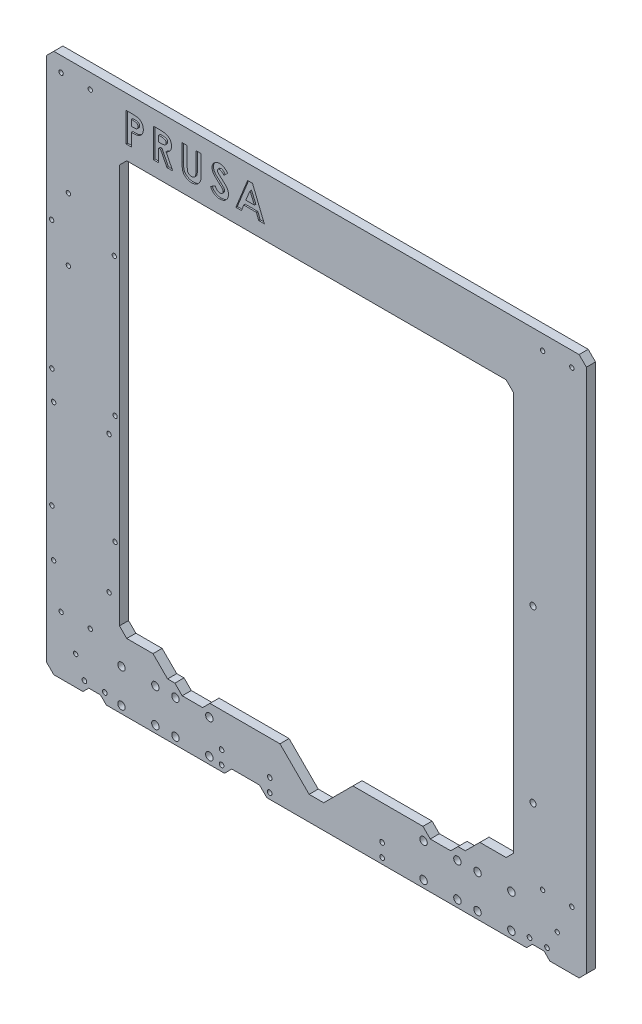
SolidWorks part; units mm, degrees
material "6063-O, Extruded Rod (SS)"
ref_plane "Front Plane" through (0, 0, 0) normal (0, 0, 1) x (1, 0, 0)
ref_plane "Top Plane" through (0, 0, 0) normal (0, 1, 0) x (1, 0, 0)
ref_plane "Right Plane" through (0, 0, 0) normal (1, 0, 0) x (0, 0, -1)
sketch "Sketch1" plane through (0, 0, 0) normal (0, 0, 1) x (1, 0, 0)
  line L0 (162, 177.023) -> (141.977, 157)
  line L1 (141.977, 157) -> (125, 157)
  line L2 (125, 157) -> (101.5, 180.5)
  line L3 (101.5, 189.5) -> (125, 213)
  line L4 (125, 213) -> (141.977, 213)
  line L5 (141.977, 213) -> (162, 192.977)
  line L6 (251.5, 210.0147) -> (240.9853, 220.5294)
  line L7 (240.9853, 220.5294) -> (224.0147, 220.5294)
  line L8 (224.0147, 220.5294) -> (197, 193.5147)
  line L9 (197, 176.4853) -> (224.0147, 149.4706)
  line L10 (224.0147, 149.4706) -> (240.9853, 149.4706)
  line L11 (240.9853, 149.4706) -> (251.5, 159.9853)
  line L12 (184.4001, 296) -> (225.4001, 255)
  line L13 (225.4001, 255) -> (241.5147, 255)
  line L14 (241.5147, 255) -> (282.5147, 296)
  line L15 (282.5147, 296) -> (287.4852, 296)
  line L16 (287.4852, 296) -> (291, 292.4852)
  line L17 (291, 292.4852) -> (291, 287.5147)
  line L18 (291, 287.5147) -> (253, 249.5147)
  line L19 (253, 249.5147) -> (253, 226.667)
  line L20 (253, 226.667) -> (291, 188.667)
  line L21 (291, 188.667) -> (291, 181.333)
  line L22 (291, 181.333) -> (253, 143.333)
  line L23 (253, 143.333) -> (253, 120.4853)
  line L24 (253, 120.4853) -> (291, 82.4853)
  line L25 (291, 82.4853) -> (291, 77.5148)
  line L26 (291, 77.5148) -> (287.4852, 74)
  line L27 (287.4852, 74) -> (282.5147, 74)
  line L28 (282.5147, 74) -> (241.5147, 115)
  line L29 (241.5147, 115) -> (225.4001, 115)
  line L30 (225.4001, 115) -> (184.4001, 74)
  line L31 (184.4001, 74) -> (175.5999, 74)
  line L32 (175.5999, 74) -> (134.5999, 115)
  line L33 (134.5999, 115) -> (113.4853, 115)
  line L34 (113.4853, 115) -> (72.4853, 74)
  line L35 (72.4853, 74) -> (67.5148, 74)
  line L36 (67.5148, 74) -> (64, 77.5148)
  line L37 (64, 77.5148) -> (64, 82.4853)
  line L38 (64, 82.4853) -> (91, 109.4853)
  line L39 (91, 109.4853) -> (91, 123)
  line L40 (91, 123) -> (81.5, 132.5)
  line L41 (81.5, 132.5) -> (81.5, 163.7609)
  line L42 (81.5, 163.7609) -> (64, 181.2609)
  line L43 (64, 188.7391) -> (81.5, 206.2391)
  line L44 (81.5, 206.2391) -> (81.5, 237.5)
  line L45 (81.5, 237.5) -> (91, 247)
  line L46 (91, 247) -> (91, 260.5147)
  line L47 (91, 260.5147) -> (64, 287.5147)
  line L48 (64, 287.5147) -> (64, 292.4852)
  line L49 (64, 292.4852) -> (67.5148, 296)
  line L50 (67.5148, 296) -> (72.4853, 296)
  line L51 (72.4853, 296) -> (113.4853, 255)
  line L52 (113.4853, 255) -> (134.5999, 255)
  line L53 (134.5999, 255) -> (175.5999, 296)
  line L54 (175.5999, 296) -> (184.4001, 296)
  line L55 (143, 246.4158) -> (143, 229.5663)
  line L56 (143, 229.5663) -> (159.5663, 213)
  line L57 (159.5663, 213) -> (199.5147, 213)
  line L58 (199.5147, 213) -> (216, 229.4853)
  line L59 (216, 229.4853) -> (216, 247.4296)
  line L60 (216, 247.4296) -> (183.6826, 279.747)
  line L61 (183.6826, 279.747) -> (176.3174, 279.7332)
  line L62 (176.3174, 279.7332) -> (143, 246.4158)
  line L63 (143, 123.5842) -> (143, 140.4337)
  line L64 (143, 140.4337) -> (159.5663, 157)
  line L65 (159.5663, 157) -> (199.5147, 157)
  line L66 (199.5147, 157) -> (216, 140.5147)
  line L67 (216, 140.5147) -> (216, 122.5704)
  line L68 (216, 122.5704) -> (183.6826, 90.253)
  line L69 (183.6826, 90.253) -> (176.3174, 90.2668)
  line L70 (176.3174, 90.2668) -> (143, 123.5842)
  line L71 (101.5, 226.75) -> (101.5, 213.25)
  line L72 (271.5, 191.75) -> (271.5, 178.25)
  line L73 (101.5, 156.75) -> (101.5, 143.25)
  line L74 (91.5, 226.75) -> (91.5, 213.25)
  line L75 (261.5, 191.75) -> (261.5, 178.25)
  line L76 (91.5, 156.75) -> (91.5, 143.25)
  line L77 (93.6792, 358.4107) -> (93.6792, 347.8262)
  line L78 (93.6792, 347.8262) -> (93.9406, 345.7354)
  line L79 (93.9406, 345.7354) -> (94.4633, 344.2327)
  line L80 (94.4633, 344.2327) -> (95.182, 343.1873)
  line L81 (95.182, 343.1873) -> (96.1846, 341.9648)
  line L82 (96.1846, 341.9648) -> (97.8105, 341.4329)
  line L83 (97.8105, 341.4329) -> (99.6248, 341.0966)
  line L84 (99.6248, 341.0966) -> (101.977, 341.3579)
  line L85 (101.977, 341.3579) -> (104.0024, 342.4033)
  line L86 (104.0024, 342.4033) -> (105.1131, 344.2327)
  line L87 (105.1131, 344.2327) -> (105.5705, 346.7155)
  line L88 (105.5705, 346.7155) -> (105.5705, 349.1983)
  line L89 (105.5705, 349.1983) -> (105.5705, 358.4107)
  line L90 (79.8932, 349.3289) -> (80.0892, 349.3289)
  line L91 (80.0892, 349.3289) -> (81.0039, 348.8063)
  line L92 (81.0039, 348.8063) -> (82.0493, 347.4342)
  line L93 (82.0493, 347.4342) -> (86.4922, 341.0966)
  line L94 (73.5556, 341.1619) -> (73.5556, 358.4107)
  line L95 (73.5556, 358.4107) -> (80.6119, 358.4107)
  line L96 (80.6119, 358.4107) -> (82.768, 357.7574)
  line L97 (82.768, 357.7574) -> (83.8134, 356.7773)
  line L98 (83.8134, 356.7773) -> (84.5321, 355.4706)
  line L99 (84.5321, 355.4706) -> (84.8588, 353.7065)
  line L100 (84.8588, 353.7065) -> (84.5321, 352.0078)
  line L101 (84.5321, 352.0078) -> (83.6827, 350.5703)
  line L102 (83.6827, 350.5703) -> (82.5067, 349.8517)
  line L103 (82.5067, 349.8517) -> (81.3306, 349.525)
  line L104 (81.3306, 349.525) -> (79.8932, 349.3289)
  line L105 (79.8932, 349.3289) -> (78.1291, 349.3289)
  line L106 (78.1291, 349.3289) -> (73.5556, 349.3289)
  line L107 (113.0897, 345.4442) -> (114.2004, 343.4842)
  line L108 (114.2004, 343.4842) -> (116.6178, 341.8507)
  line L109 (116.6178, 341.8507) -> (118.9699, 341.1974)
  line L110 (118.9699, 341.1974) -> (122.4328, 341.7201)
  line L111 (122.4328, 341.7201) -> (124.0662, 343.0268)
  line L112 (124.0662, 343.0268) -> (125.2422, 345.1176)
  line L113 (125.2422, 345.1176) -> (125.2422, 346.359)
  line L114 (125.2422, 346.359) -> (124.9156, 347.4697)
  line L115 (124.9156, 347.4697) -> (123.7395, 348.7764)
  line L116 (123.7395, 348.7764) -> (122.5635, 349.2991)
  line L117 (122.5635, 349.2991) -> (116.7485, 351.0632)
  line L118 (116.7485, 351.0632) -> (115.0497, 352.1739)
  line L119 (115.0497, 352.1739) -> (114.0044, 353.4153)
  line L120 (114.0044, 353.4153) -> (113.8737, 354.5914)
  line L121 (113.8737, 354.5914) -> (114.135, 356.3554)
  line L122 (114.135, 356.3554) -> (115.3764, 357.6622)
  line L123 (115.3764, 357.6622) -> (117.4672, 358.4462)
  line L124 (117.4672, 358.4462) -> (120.0807, 358.5769)
  line L125 (120.0807, 358.5769) -> (122.8248, 357.8582)
  line L126 (122.8248, 357.8582) -> (123.9355, 356.8128)
  line L127 (123.9355, 356.8128) -> (124.3929, 355.5714)
  line L128 (130.9954, 341.0312) -> (137.9864, 358.5414)
  line L129 (137.9864, 358.5414) -> (139.0972, 358.5414)
  line L130 (139.0972, 358.5414) -> (145.9575, 341.0312)
  line L131 (143.9343, 346.1951) -> (133.0803, 346.1927)
  line L132 (55, 341.1619) -> (55, 358.4107)
  line L133 (55, 358.4107) -> (62.0563, 358.4107)
  line L134 (62.0563, 358.4107) -> (64.2125, 357.7574)
  line L135 (64.2125, 357.7574) -> (65.2578, 356.7773)
  line L136 (65.2578, 356.7773) -> (65.9765, 355.4706)
  line L137 (65.9765, 355.4706) -> (66.3032, 353.7065)
  line L138 (66.3032, 353.7065) -> (65.9765, 352.0078)
  line L139 (65.9765, 352.0078) -> (65.1272, 350.5703)
  line L140 (65.1272, 350.5703) -> (63.9511, 349.8517)
  line L141 (63.9511, 349.8517) -> (62.7751, 349.525)
  line L142 (62.7751, 349.525) -> (61.3376, 349.3289)
  line L143 (61.3376, 349.3289) -> (59.5735, 349.3289)
  line L144 (59.5735, 349.3289) -> (55, 349.3289)
  line L145 (251.5, 210.0147) -> (251.5, 159.9853)
  line L146 (197, 193.5147) -> (197, 176.4853)
  line L147 (64, 188.7391) -> (64, 181.2609)
  line L148 (101.5, 189.5) -> (101.5, 180.5)
  line L149 (162, 192.977) -> (162, 177.023)
  line L150 (102.1, 142.75) -> (102, 142.75)
  line L151 (272.1, 177.75) -> (272, 177.75)
  line L152 (102.1, 212.75) -> (102, 212.75)
  line L153 (90.9, 142.75) -> (91, 142.75)
  line L154 (260.9, 177.75) -> (261, 177.75)
  line L155 (90.9, 212.75) -> (91, 212.75)
  line L156 (102, 142.75) -> (101.5, 143.25)
  line L157 (272, 177.75) -> (271.5, 178.25)
  line L158 (102, 212.75) -> (101.5, 213.25)
  line L159 (91, 142.75) -> (91.5, 143.25)
  line L160 (261, 177.75) -> (261.5, 178.25)
  line L161 (91, 212.75) -> (91.5, 213.25)
  line L162 (102.1, 157.25) -> (102, 157.25)
  line L163 (272.1, 192.25) -> (272, 192.25)
  line L164 (102.1, 227.25) -> (102, 227.25)
  line L165 (90.9, 157.25) -> (91, 157.25)
  line L166 (260.9, 192.25) -> (261, 192.25)
  line L167 (90.9, 227.25) -> (91, 227.25)
  line L168 (101.5, 156.75) -> (102, 157.25)
  line L169 (271.5, 191.75) -> (272, 192.25)
  line L170 (101.5, 226.75) -> (102, 227.25)
  line L171 (91.5, 156.75) -> (91, 157.25)
  line L172 (261.5, 191.75) -> (261, 192.25)
  line L173 (91.5, 226.75) -> (91, 227.25)
  line L174 (90.9, 163.25) -> (102.1, 163.25)
  line L175 (260.9, 198.25) -> (272.1, 198.25)
  line L176 (90.9, 233.25) -> (102.1, 233.25)
  line L177 (90.9, 136.75) -> (102.1, 136.75)
  line L178 (260.9, 171.75) -> (272.1, 171.75)
  line L179 (90.9, 206.75) -> (102.1, 206.75)
  arc A0 (102.1, 206.75) -> (102.1, 212.75) centre (102.1, 209.75) ccw
  arc A1 (272.1, 171.75) -> (272.1, 177.75) centre (272.1, 174.75) ccw
  arc A2 (102.1, 136.75) -> (102.1, 142.75) centre (102.1, 139.75) ccw
  arc A3 (90.9, 142.75) -> (90.9, 136.75) centre (90.9, 139.75) ccw
  arc A4 (90.9, 212.75) -> (90.9, 206.75) centre (90.9, 209.75) ccw
  arc A5 (260.9, 177.75) -> (260.9, 171.75) centre (260.9, 174.75) ccw
  arc A6 (102.1, 157.25) -> (102.1, 163.25) centre (102.1, 160.25) ccw
  arc A7 (102.1, 227.25) -> (102.1, 233.25) centre (102.1, 230.25) ccw
  arc A8 (272.1, 192.25) -> (272.1, 198.25) centre (272.1, 195.25) ccw
  arc A9 (90.9, 163.25) -> (90.9, 157.25) centre (90.9, 160.25) ccw
  arc A10 (260.9, 198.25) -> (260.9, 192.25) centre (260.9, 195.25) ccw
  arc A11 (90.9, 233.25) -> (90.9, 227.25) centre (90.9, 230.25) ccw
  circle A12 centre (318.6, 4.9) radius 2.55
  circle A13 centre (318.6, 28.1) radius 2.55
  circle A14 centre (295.4, 28.1) radius 2.55
  circle A15 centre (295.4, 4.9) radius 2.55
  circle A16 centre (281.6, 4.9) radius 2.55
  circle A17 centre (258.4, 4.9) radius 2.55
  circle A18 centre (258.4, 28.1) radius 2.55
  circle A19 centre (281.6, 28.1) radius 2.55
  circle A20 centre (111.6, 4.9) radius 2.55
  circle A21 centre (111.6, 28.1) radius 2.55
  circle A22 centre (88.4, 28.1) radius 2.55
  circle A23 centre (88.4, 4.9) radius 2.55
  circle A24 centre (74.6, 4.9) radius 2.55
  circle A25 centre (74.6, 28.1) radius 2.55
  circle A26 centre (51.4, 28.1) radius 2.55
  circle A27 centre (51.4, 4.9) radius 2.55
  circle A28 centre (360, 39.8) radius 1.5
  circle A29 centre (10, 39.8) radius 1.5
  circle A30 centre (340, 359.8) radius 1.5
  circle A31 centre (30, 39.8) radius 1.5
  circle A32 centre (42.9, 67.8) radius 1.5
  circle A33 centre (340, 39.8) radius 1.5
  circle A34 centre (10, 359.8) radius 1.5
  circle A35 centre (350, 19.8) radius 1.5
  circle A36 centre (47, 99.8) radius 1.5
  circle A37 centre (3.7, 181.1) radius 1.5
  circle A38 centre (20, 19.8) radius 1.5
  circle A39 centre (4.9, 67.8) radius 1.5
  circle A40 centre (360, 359.8) radius 1.5
  circle A41 centre (42.9, 161.8) radius 1.5
  circle A42 centre (3.7, 99.8) radius 1.5
  circle A43 centre (30, 359.8) radius 1.5
  circle A44 centre (47, 174.7) radius 1.5
  circle A45 centre (4.9, 161.8) radius 1.5
  circle A46 centre (46.5, 269.3) radius 1.5
  circle A47 centre (15, 247.8) radius 1.5
  circle A48 centre (3.5, 269.3) radius 1.5
  circle A49 centre (15, 290.8) radius 1.5
  circle A50 centre (180, 80) radius 1.5
  circle A51 centre (180, 290) radius 1.5
  circle A52 centre (285, 80) radius 1.5
  circle A53 centre (70, 290) radius 1.5
  circle A54 centre (285, 290) radius 1.5
  circle A55 centre (70, 185) radius 1.5
  circle A56 centre (180, 185) radius 1.5
  circle A57 centre (285, 185) radius 1.5
  circle A58 centre (256.5, 185) radius 1.6
  circle A59 centre (276.5, 185) radius 1.6
  circle A60 centre (106.5, 220) radius 1.6
  circle A61 centre (106.5, 150) radius 1.6
  circle A62 centre (86.5, 220) radius 1.6
  circle A63 centre (86.5, 150) radius 1.6
  circle A64 centre (70, 80) radius 1.5
  circle A65 centre (181.5, 165.5) radius 1.5
  circle A66 centre (181.5, 204.5) radius 1.5
  circle A67 centre (40, 7) radius 1.6
  circle A68 centre (331, 7) radius 1.6
  circle A69 centre (343, 7) radius 1.6
  circle A70 centre (120, 13) radius 1.6
  circle A71 centre (120, 4) radius 1.6
  circle A72 centre (230, 13) radius 1.6
  circle A73 centre (230, 4) radius 1.6
  circle A74 centre (333.4, 205) radius 2.1
  circle A75 centre (333.4, 88) radius 2.1
  circle A76 centre (26, 7) radius 1.6
  circle A77 centre (153, 13) radius 1.6
  circle A78 centre (153, 4) radius 1.6
  spline S0 degree 2 poles (5, 370) (2.5, 367.5) (0, 365) knots 1472.868668 1472.868668 1472.868668 1479.939736 1479.939736 1479.939736
  spline S1 degree 2 poles (365, 370) (185, 370) (5, 370) knots 1112.868668 1112.868668 1112.868668 1472.868668 1472.868668 1472.868668
  spline S2 degree 2 poles (370, 365) (367.5, 367.5) (365, 370) knots 1105.7976 1105.7976 1105.7976 1112.868668 1112.868668 1112.868668
  spline S3 degree 2 poles (370, 5) (370, 185) (370, 365) knots 745.7976 745.7976 745.7976 1105.7976 1105.7976 1105.7976
  spline S4 degree 2 poles (365, 0) (367.5, 2.5) (370, 5) knots 738.726533 738.726533 738.726533 745.7976 745.7976 745.7976
  spline S5 degree 2 poles (345, 0) (355, 0) (365, 0) knots 718.726533 718.726533 718.726533 738.726533 738.726533 738.726533
  spline S6 degree 2 poles (341, 4) (343, 2) (345, 0) knots 710.241251 710.241251 710.241251 718.726533 718.726533 718.726533
  spline S7 degree 2 poles (333, 4) (337, 4) (341, 4) knots 704.241251 704.241251 704.241251 710.241251 710.241251 710.241251
  spline S8 degree 2 poles (329, 0) (331, 2) (333, 4) knots 698.584397 698.584397 698.584397 704.241251 704.241251 704.241251
  spline S9 degree 2 poles (151, 0) (240, 0) (329, 0) knots 507.584397 507.584397 507.584397 698.584397 698.584397 698.584397
  spline S10 degree 2 poles (146, 5) (148.5, 2.5) (151, 0) knots 501.927543 501.927543 501.927543 507.584397 507.584397 507.584397
  spline S11 degree 2 poles (127, 5) (136.5, 5) (146, 5) knots 487.927543 487.927543 487.927543 501.927543 501.927543 501.927543
  spline S12 degree 2 poles (122, 0) (124.5, 2.5) (127, 5) knots 482.270688 482.270688 482.270688 487.927543 487.927543 487.927543
  spline S13 degree 2 poles (41, 0) (81.5, 0) (122, 0) knots 407.270688 407.270688 407.270688 482.270688 482.270688 482.270688
  spline S14 degree 2 poles (37, 4) (39, 2) (41, 0) knots 401.613834 401.613834 401.613834 407.270688 407.270688 407.270688
  spline S15 degree 2 poles (29, 4) (33, 4) (37, 4) knots 395.613834 395.613834 395.613834 401.613834 401.613834 401.613834
  spline S16 degree 2 poles (25, 0) (27, 2) (29, 4) knots 387.128553 387.128553 387.128553 395.613834 395.613834 395.613834
  spline S17 degree 2 poles (5, 0) (15, 0) (25, 0) knots 367.128553 367.128553 367.128553 387.128553 387.128553 387.128553
  spline S18 degree 2 poles (0, 5) (2.5, 2.5) (5, 0) knots 360.191742 360.191742 360.191742 367.128553 367.128553 367.128553
  spline S19 degree 2 poles (0, 365) (0, 185) (0, 5) knots 0 0 0 360.191742 360.191742 360.191742
  spline S20 degree 2 poles (93, 31.5) (100, 31.5) (107, 31.5) knots 1110.421356 1110.421356 1110.421356 1117.046356 1117.046356 1117.046356
  spline S21 degree 2 poles (88, 36.5) (90.5, 34) (93, 31.5) knots 1103.350288 1103.350288 1103.350288 1110.421356 1110.421356 1110.421356
  spline S22 degree 2 poles (83, 36.5) (85.5, 36.5) (88, 36.5) knots 1098.350288 1098.350288 1098.350288 1103.350288 1103.350288 1103.350288
  spline S23 degree 2 poles (73, 46.5) (78, 41.5) (83, 36.5) knots 1084.208153 1084.208153 1084.208153 1098.350288 1098.350288 1098.350288
  spline S24 degree 2 poles (55, 46.5) (64, 46.5) (73, 46.5) knots 1066.208153 1066.208153 1066.208153 1084.208153 1084.208153 1084.208153
  spline S25 degree 2 poles (50, 51.5) (52.5, 49) (55, 46.5) knots 1059.137085 1059.137085 1059.137085 1066.208153 1066.208153 1066.208153
  spline S26 degree 2 poles (50, 325) (50, 188.25) (50, 51.5) knots 787.637085 787.637085 787.637085 1059.137085 1059.137085 1059.137085
  spline S27 degree 2 poles (55, 330) (52.5, 327.5) (50, 325) knots 780.566017 780.566017 780.566017 787.637085 787.637085 787.637085
  spline S28 degree 2 poles (315, 330) (185, 330) (55, 330) knots 520.566017 520.566017 520.566017 780.566017 780.566017 780.566017
  spline S29 degree 2 poles (320, 325) (317.5, 327.5) (315, 330) knots 513.494949 513.494949 513.494949 520.566017 520.566017 520.566017
  spline S30 degree 2 poles (320, 51.5) (320, 188.25) (320, 325) knots 241.994949 241.994949 241.994949 513.494949 513.494949 513.494949
  spline S31 degree 2 poles (315, 46.5) (317.5, 49) (320, 51.5) knots 234.923882 234.923882 234.923882 241.994949 241.994949 241.994949
  spline S32 degree 2 poles (297, 46.5) (306, 46.5) (315, 46.5) knots 216.923882 216.923882 216.923882 234.923882 234.923882 234.923882
  spline S33 degree 2 poles (287, 36.5) (292, 41.5) (297, 46.5) knots 202.781746 202.781746 202.781746 216.923882 216.923882 216.923882
  spline S34 degree 2 poles (282, 36.5) (284.5, 36.5) (287, 36.5) knots 197.781746 197.781746 197.781746 202.781746 202.781746 202.781746
  spline S35 degree 2 poles (277, 31.5) (279.5, 34) (282, 36.5) knots 190.710678 190.710678 190.710678 197.781746 197.781746 197.781746
  spline S36 degree 2 poles (263, 31.5) (264, 31.5) (265, 31.5) (270, 31.5) (275, 31.5) (276, 31.5) (277, 31.5) knots 176.710678 176.710678 176.710678 178.710678 178.710678 188.710678 188.710678 190.710678 190.710678 190.710678
  spline S37 degree 2 poles (258, 36.5) (260.5, 34) (263, 31.5) knots 169.63961 169.63961 169.63961 176.710678 176.710678 176.710678
  spline S38 degree 2 poles (210, 36.5) (211.75, 36.5) (213.5, 36.5) (235.75, 36.5) (258, 36.5) knots 121.63961 121.63961 121.63961 125.13961 125.13961 169.63961 169.63961 169.63961
  spline S39 degree 2 poles (190, 16.5) (200, 26.5) (210, 36.5) knots 93.355339 93.355339 93.355339 121.63961 121.63961 121.63961
  spline S40 degree 2 poles (180, 16.5) (185, 16.5) (190, 16.5) knots 83.355339 83.355339 83.355339 93.355339 93.355339 93.355339
  spline S41 degree 2 poles (160, 36.5) (170, 26.5) (180, 16.5) knots 55.071068 55.071068 55.071068 83.355339 83.355339 83.355339
  spline S42 degree 2 poles (112, 36.5) (134.25, 36.5) (156.5, 36.5) (158.25, 36.5) (160, 36.5) knots 7.071068 7.071068 7.071068 51.571068 51.571068 55.071068 55.071068 55.071068
  spline S43 degree 2 poles (107, 31.5) (109.5, 34) (112, 36.5) knots 0 0 0 7.071068 7.071068 7.071068
extrude "Boss-Extrude1" add sketch "Sketch1" along normal blind 6.25
sketch "Sketch2" plane through (0, 0, 6.25) normal (0, 0, 1) x (1, 0, 0)
  text T0 "<b>PRUSA</b>" font "Century Gothic" height 20
extrude "Cut-Extrude1" cut sketch "Sketch2" against normal blind 1
